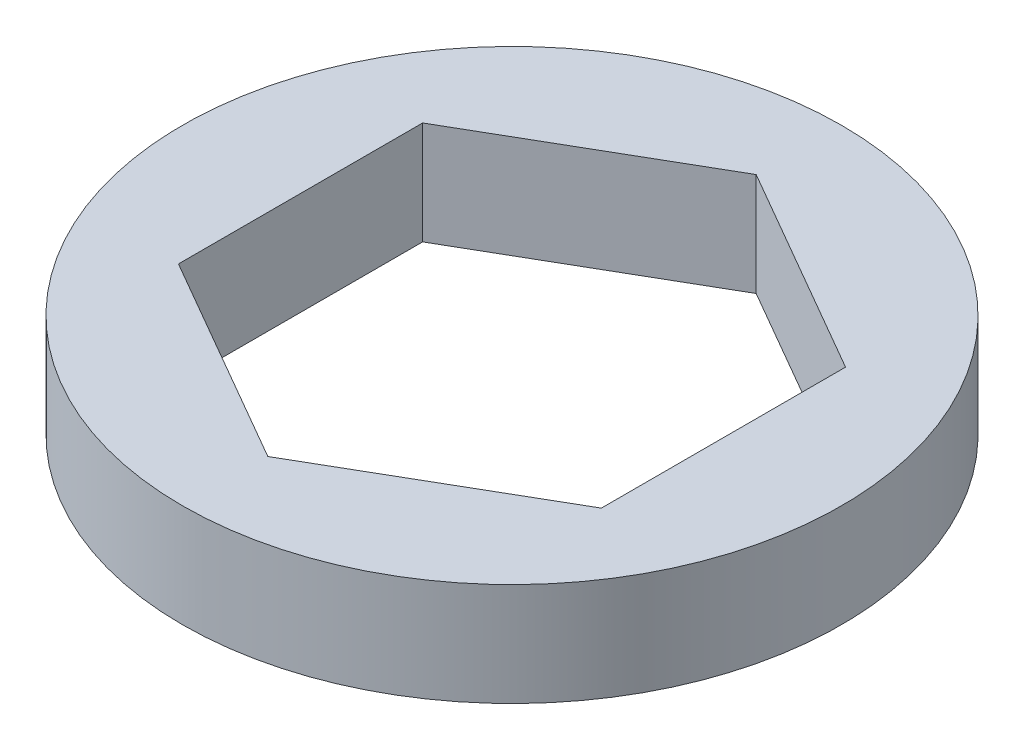
SolidWorks part; units mm, degrees
ref_plane "Front Plane" through (0, 0, 0) normal (0, 0, 1) x (1, 0, 0)
ref_plane "Top Plane" through (0, 0, 0) normal (0, 1, 0) x (1, 0, 0)
ref_plane "Right Plane" through (0, 0, 0) normal (1, 0, 0) x (0, 0, -1)
sketch "Sketch1" plane through (0, 0, 0) normal (0, 1, 0) x (1, 0, 0)
  line L1 (0, 5.4993) -> (-4.7625, 2.7496)
  line L2 (-4.7625, 2.7496) -> (-4.7625, -2.7496)
  line L3 (-4.7625, -2.7496) -> (0, -5.4993)
  line L4 (0, -5.4993) -> (4.7625, -2.7496)
  line L5 (4.7625, -2.7496) -> (4.7625, 2.7496)
  line L6 (4.7625, 2.7496) -> (0, 5.4993)
  circle A0 centre (0, 0) radius 4.7625 construction
  point P1 (0, 0)
  dimension "D1" = 9.525
sketch "Sketch2" plane through (0, 0, 0) normal (0, 1, 0) x (1, 0, 0)
  line L12 (0, 5.7192) -> (-4.953, 2.8596)
  line L13 (4.953, 2.8596) -> (0, 5.7192)
  line L14 (4.953, -2.8596) -> (4.953, 2.8596)
  line L15 (0, -5.7192) -> (4.953, -2.8596)
  line L16 (-4.953, -2.8596) -> (0, -5.7192)
  line L17 (-4.953, 2.8596) -> (-4.953, -2.8596)
  line L18 (0, 5.7192) -> (-4.953, 2.8596)
  line L19 (4.953, 2.8596) -> (0, 5.7192)
  line L20 (4.953, -2.8596) -> (4.953, 2.8596)
  line L21 (0, -5.7192) -> (4.953, -2.8596)
  line L22 (-4.953, -2.8596) -> (0, -5.7192)
  line L23 (-4.953, 2.8596) -> (-4.953, -2.8596)
  circle A0 centre (0, 0) radius 7.7192
  dimension "D2" = 2
  dimension "D1" = 0.1905
extrude "Boss-Extrude1" add sketch "Sketch2" along normal blind 2.413
